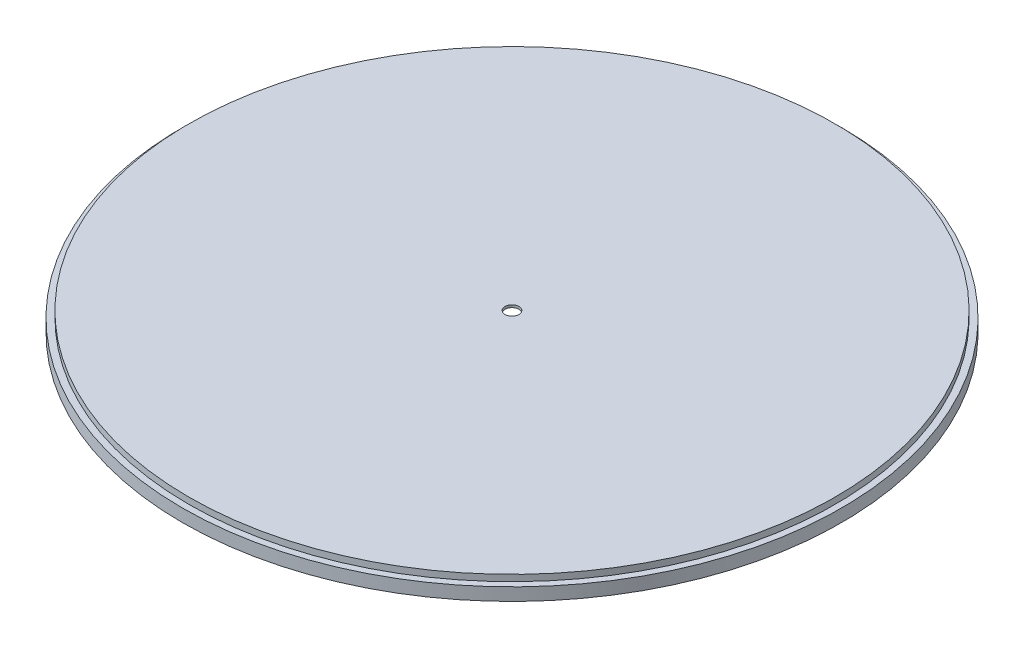
SolidWorks part; units mm, degrees
ref_plane "Front Plane" through (0, 0, 0) normal (0, 0, 1) x (1, 0, 0)
ref_plane "Top Plane" through (0, 0, 0) normal (0, 1, 0) x (1, 0, 0)
ref_plane "Right Plane" through (0, 0, 0) normal (1, 0, 0) x (0, 0, -1)
sketch "Sketch1" plane through (0, 0, 0) normal (0, 1, 0) x (1, 0, 0)
  circle A0 centre (0, 0) radius 25.5
  dimension "D1" = 51
extrude "Boss-Extrude1" add sketch "Sketch1" against normal blind 1.5
sketch "Sketch2" plane through (0, -1.5, 0) normal (0, -1, 0) x (-1, 0, 0)
  circle A0 centre (0, 0) radius 26
  circle A1 centre (0, 0) radius 25.5
  circle A2 centre (0, 0) radius 25.5
  dimension "D1" = 0
  dimension "D2" = 0.5
extrude "Boss-Extrude2" add sketch "Sketch2" against normal blind 1 contours A0
sketch "Sketch3" plane through (0, -0.5, 0) normal (0, 1, 0) x (1, 0, 0)
  circle A0 centre (0, 0) radius 0.55
  dimension "D1" = 1.1
extrude "Cut-Extrude1" cut sketch "Sketch3" against normal through all
sketch "Sketch4" plane through (0, 0, 0) normal (0, 0, 1) x (1, 0, 0)
  line L8 (-4.35, -1.5) -> (0, -1.5)
  line L9 (-4.35, -1.5) -> (-0.55, -0.2)
  line L11 (-0.55, -0.2) -> (-0.55, 0)
  line L12 (-0.55, 0) -> (0, 0)
  line L13 (0, -1.5) -> (0, 0)
  line L15 (0, -0.5) -> (0, -1.5) construction
  line L16 (-26, -1.5) -> (26, -1.5) construction
  dimension "D1" = 4.35
  dimension "D2" = 0.55
  dimension "D4" = 0.2
revolve "Cut-Revolve1" cut sketch "Sketch4" angle 360 about L13
